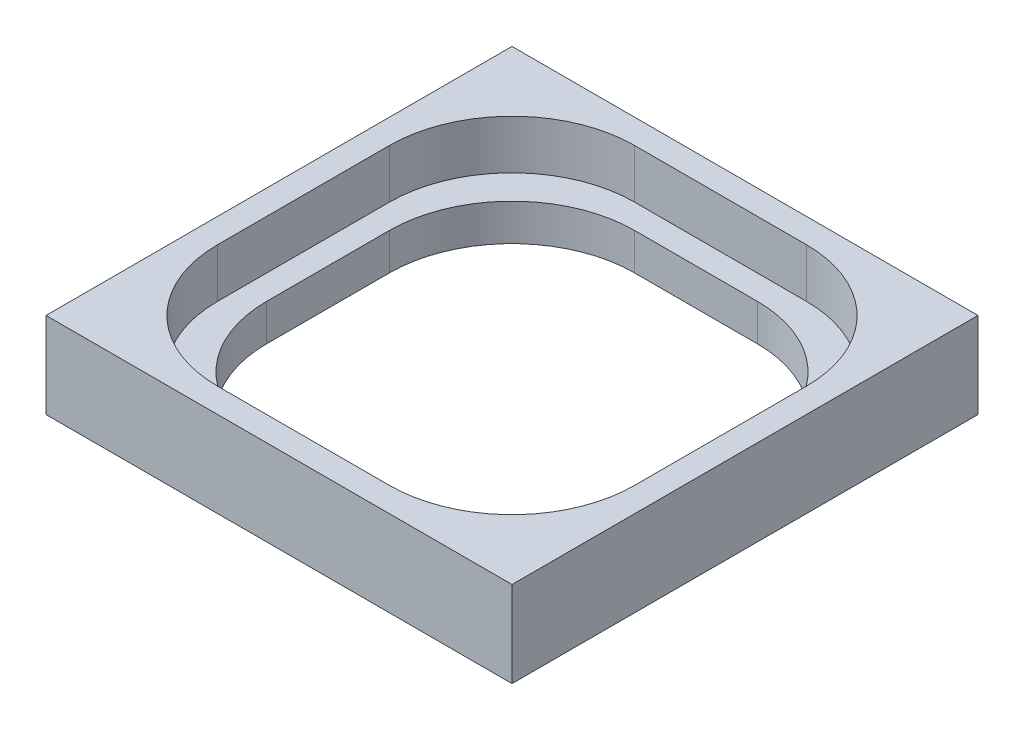
SolidWorks part; units mm, degrees
ref_plane "Front Plane" through (0, 0, 0) normal (0, 0, 1) x (1, 0, 0)
ref_plane "Top Plane" through (0, 0, 0) normal (0, 1, 0) x (1, 0, 0)
ref_plane "Right Plane" through (0, 0, 0) normal (1, 0, 0) x (0, 0, -1)
sketch "Sketch1" plane through (0, 0, 0) normal (0, 1, 0) x (1, 0, 0)
  line L0 (14, 34) -> (24, 34)
  line L1 (0, 0) -> (38, 0)
  line L2 (0, 0) -> (0, 38)
  line L3 (0, 38) -> (38, 38)
  line L4 (38, 0) -> (38, 38)
  line L5 (34, 14) -> (34, 24)
  line L6 (14, 4) -> (24, 4)
  line L7 (4, 14) -> (4, 24)
  line L8 (4, 4) -> (34, 4) construction
  line L9 (4, 4) -> (4, 34) construction
  line L10 (34, 4) -> (34, 34) construction
  line L11 (4, 34) -> (34, 34) construction
  arc A0 (14, 4) -> (4, 14) centre (14, 14) cw
  arc A1 (34, 14) -> (24, 4) centre (24, 14) cw
  arc A2 (24, 34) -> (34, 24) centre (24, 24) cw
  arc A3 (14, 34) -> (4, 24) centre (14, 24) ccw
  dimension "D3" = 10
  dimension "D1" = 38
  dimension "D2" = 4
extrude "Boss-Extrude1" add sketch "Sketch1" along normal blind 3 contours L2 L3 L4 L1 | L7 A3 L0 A2 L5 A1 L6 A0
sketch "Sketch2" plane through (0, 3, 0) normal (0, 1, 0) x (1, 0, 0)
  line L0 (38, 0) -> (38, 38) construction
  line L1 (0, 38) -> (38, 38)
  line L2 (0, 38) -> (0, 0)
  line L3 (0, 0) -> (38, 0)
  line L4 (38, 38) -> (38, 0)
  line L5 (12, 36) -> (26, 36)
  line L6 (36, 26) -> (36, 12)
  line L7 (12, 2) -> (26, 2)
  line L8 (2, 26) -> (2, 12)
  line L9 (2, 36) -> (36, 36) construction
  line L10 (36, 36) -> (36, 2) construction
  line L11 (2, 2) -> (36, 2) construction
  line L12 (2, 36) -> (2, 2) construction
  arc A0 (26, 36) -> (36, 26) centre (26, 26) cw
  arc A1 (36, 12) -> (26, 2) centre (26, 12) cw
  arc A2 (12, 2) -> (2, 12) centre (12, 12) cw
  arc A3 (12, 36) -> (2, 26) centre (12, 26) ccw
  dimension "D2" = 10
  dimension "D1" = 2
extrude "Boss-Extrude2" add sketch "Sketch2" along normal blind 4
